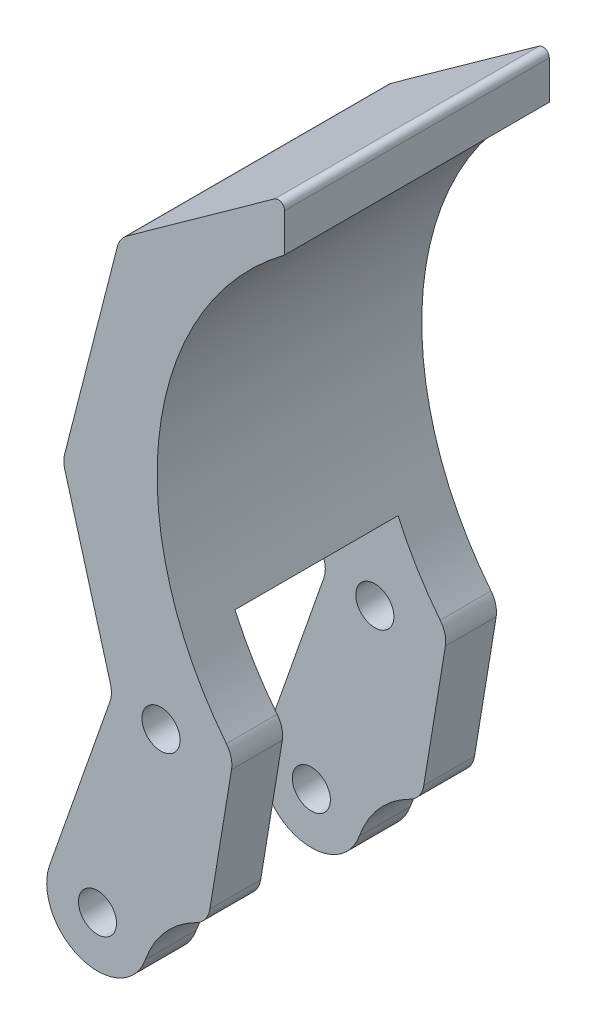
SolidWorks part; units mm, degrees
material "PMMA"
ref_plane "前视基准面" through (0, 0, 0) normal (0, 0, 1) x (1, 0, 0)
ref_plane "上视基准面" through (0, 0, 0) normal (0, 1, 0) x (1, 0, 0)
ref_plane "右视基准面" through (0, 0, 0) normal (1, 0, 0) x (0, 0, -1)
sketch "草图1" plane through (0, 0, 0) normal (0, 0, 1) x (1, 0, 0)
  line L1 (-44.759, 0) -> (37.6123, 0) construction
  line L2 (0, 0) -> (0, 68.6572) construction
  line L3 (23.6847, 21.3009) -> (7.0185, 2.6666) construction
  line L4 (29.6477, 15.9677) -> (12.9815, -2.6666) construction
  line L5 (30.4405, 19.9591) -> (22.8919, 17.3096) construction
  line L6 (16.1103, 33.6542) -> (17.8145, 23.2934) construction
  line L8 (30.4405, 19.9591) -> (25.6815, 33.5175) construction
  line L9 (25.6428, 34.7197) -> (29.2417, 47.5584) construction
  line L10 (29.2536, 48.5936) -> (25.1082, 64.8082) construction
  line L11 (19.8028, 35.3009) -> (3.1366, 16.6666) construction
  line L12 (23.5296, 31.9677) -> (6.8634, 13.3334) construction
  line L13 (24.3365, 65.9378) -> (12.7194, 74.273) construction
  line L14 (11.9279, 73.8667) -> (11.9279, 70.8409) construction
  line L15 (-23.6847, 21.3009) -> (-7.0185, 2.6666) construction
  line L16 (-29.6477, 15.9677) -> (-12.9815, -2.6666) construction
  line L17 (-23.5296, 31.9677) -> (-6.8634, 13.3334) construction
  line L18 (-19.8028, 35.3009) -> (-3.1366, 16.6666) construction
  line L19 (-16.1103, 33.6542) -> (-17.8145, 23.2934)
  line L20 (-30.4405, 19.9591) -> (-25.6815, 33.5175)
  line L25 (-25.6428, 34.7197) -> (-29.2417, 47.5584)
  line L26 (-5, 15) -> (-10, 0) construction
  line L27 (5, 15) -> (10, 0) construction
  line L28 (21.6662, 33.6343) -> (26.6662, 18.6343) construction
  line L29 (-29.2536, 48.5936) -> (-25.1082, 64.8082)
  line L30 (-24.3365, 65.9378) -> (-12.7194, 74.273)
  line L31 (-11.9279, 73.8667) -> (-11.9279, 70.8409)
  line L32 (-3.0291, 50.8087) -> (14.3488, 56.1034) construction
  circle A0 centre (-10, 0) radius 10 construction
  circle A4 centre (0, 51.7316) radius 15 construction
  circle A5 centre (10, 0) radius 4 construction
  circle A6 centre (10, 0) radius 10 construction
  arc A14 (22.8919, 17.3096) -> (17.993, 22.2086) centre (15.3434, 14.6601) ccw construction
  circle A16 centre (26.6662, 18.6343) radius 1.5 construction
  circle A17 centre (26.6662, 18.6343) radius 4 construction
  circle A18 centre (5, 15) radius 2.5 construction
  arc A19 (16.5198, 35.2255) -> (11.9279, 70.8409) centre (-3.0291, 50.8087) ccw construction
  circle A20 centre (21.6662, 33.6343) radius 2.5 construction
  circle A21 centre (-10, 0) radius 4 construction
  circle A22 centre (-26.6662, 18.6343) radius 1.5
  arc A23 (-30.4405, 19.9591) -> (-22.8919, 17.3096) centre (-26.6662, 18.6343) ccw
  arc A24 (-22.8919, 17.3096) -> (-18.8991, 21.8265) centre (-15.3434, 14.6601) cw
  circle A25 centre (-21.6662, 33.6343) radius 2.5 construction
  circle A26 centre (-5, 15) radius 2.5 construction
  circle A28 centre (-21.6662, 33.6343) radius 1.5
  circle A29 centre (-5, 15) radius 1.5 construction
  circle A30 centre (5, 15) radius 1.5 construction
  circle A31 centre (21.6662, 33.6343) radius 1.5 construction
  arc A33 (-18.8991, 21.8265) -> (-17.8145, 23.2934) centre (-19.788, 23.6181) ccw
  arc A40 (12.7194, 74.273) -> (11.9279, 73.8667) centre (12.4279, 73.8667) ccw construction
  arc A41 (18.8991, 21.8265) -> (17.8145, 23.2934) centre (19.788, 23.6181) cw construction
  arc A42 (16.1103, 33.6542) -> (16.5198, 35.2255) centre (18.0838, 33.9788) cw construction
  arc A43 (-16.5198, 35.2255) -> (-11.9279, 70.8409) centre (3.0291, 50.8087) cw
  arc A44 (25.6815, 33.5175) -> (25.6428, 34.7197) centre (27.5686, 34.1799) cw construction
  arc A45 (29.2417, 47.5584) -> (29.2536, 48.5936) centre (27.316, 48.0982) ccw construction
  arc A46 (25.1082, 64.8082) -> (24.3365, 65.9378) centre (23.1706, 64.3128) ccw construction
  arc A47 (-12.7194, 74.273) -> (-11.9279, 73.8667) centre (-12.4279, 73.8667) cw
  arc A48 (-16.1103, 33.6542) -> (-16.5198, 35.2255) centre (-18.0838, 33.9788) ccw
  arc A49 (-25.6815, 33.5175) -> (-25.6428, 34.7197) centre (-27.5686, 34.1799) ccw
  arc A50 (-29.2417, 47.5584) -> (-29.2536, 48.5936) centre (-27.316, 48.0982) cw
  arc A51 (-25.1082, 64.8082) -> (-24.3365, 65.9378) centre (-23.1706, 64.3128) cw
  point P93 (11.9279, 74.8409)
  point P96 (15.9627, 34.5512)
  point P99 (25.4726, 34.1125)
  point P102 (29.3864, 48.0744)
  point P105 (24.9279, 65.5135)
  point P109 (-11.9279, 74.8409)
  point P112 (-15.9627, 34.5512)
  point P115 (-25.4726, 34.1125)
  point P118 (-17.993, 22.2086)
  point P122 (-29.3864, 48.0744)
  point P125 (-24.9279, 65.5135)
  dimension "D1" = 30
  dimension "D3" = 20
  dimension "D4" = 25
  dimension "D5" = 8
  dimension "D6" = 3
  dimension "D7" = 2
  dimension "D8" = 8
  dimension "D13" = 25
  dimension "D20" = 140
  dimension "D21" = 5
  dimension "D27" = 3
  dimension "D29" = 0.5
  dimension "D28" = 16
  dimension "D30" = 2
  dimension "D14" = 4
  dimension "D12" = 10.5
  dimension "D18" = 150
  dimension "D10" = 0.5
  dimension "D26" = 2
  dimension "D9" = 11
  dimension "D11" = 15
  dimension "D15" = 10
  dimension "D16" = 145
  dimension "D17" = 14.5
  dimension "D19" = 18
  dimension "D22" = 5
  dimension "D23" = 15
  dimension "D24" = 25
  dimension "D25" = 3.75
extrude "凸台-拉伸1" add sketch "草图1" along normal blind 4
sketch "草图2" plane through (0, 0, 0) normal (0, 0, 1) x (1, 0, 0)
  line L0 (-26.7731, 38.7518) -> (-19.8346, 40.6968)
  line L1 (-29.2417, 47.5584) -> (-26.7731, 38.7518)
  line L6 (-11.9279, 70.8409) -> (-11.9279, 73.8667)
  line L7 (-12.7194, 74.273) -> (-24.3365, 65.9378)
  line L8 (-25.1082, 64.8082) -> (-29.2536, 48.5936)
  line L9 (-29.2417, 47.5584) -> (-25.6428, 34.7197)
  line L10 (-25.6815, 33.5175) -> (-30.4405, 19.9591)
  line L11 (-17.8145, 23.2934) -> (-16.1103, 33.6542)
  line L12 (-11.9279, 70.8409) -> (-11.9279, 73.8667)
  line L13 (-12.7194, 74.273) -> (-24.3365, 65.9378)
  line L14 (-25.1082, 64.8082) -> (-29.2536, 48.5936)
  arc A9 (-11.9279, 70.8409) -> (-16.5198, 35.2255) centre (3.0291, 50.8087) ccw
  arc A10 (-11.9279, 73.8667) -> (-12.7194, 74.273) centre (-12.4279, 73.8667) ccw
  arc A11 (-24.3365, 65.9378) -> (-25.1082, 64.8082) centre (-23.1706, 64.3128) ccw
  arc A12 (-29.2536, 48.5936) -> (-29.2417, 47.5584) centre (-27.316, 48.0982) ccw
  arc A13 (-25.6815, 33.5175) -> (-25.6428, 34.7197) centre (-27.5686, 34.1799) ccw
  arc A14 (-30.4405, 19.9591) -> (-22.8919, 17.3096) centre (-26.6662, 18.6343) ccw
  arc A15 (-18.8991, 21.8265) -> (-22.8919, 17.3096) centre (-15.3434, 14.6601) ccw
  arc A16 (-18.8991, 21.8265) -> (-17.8145, 23.2934) centre (-19.788, 23.6181) ccw
  arc A17 (-16.1103, 33.6542) -> (-16.5198, 35.2255) centre (-18.0838, 33.9788) ccw
  arc A18 (-11.9279, 70.8409) -> (-19.8346, 40.6968) centre (3.0291, 50.8087) ccw
  arc A19 (-11.9279, 73.8667) -> (-12.7194, 74.273) centre (-12.4279, 73.8667) ccw
  arc A20 (-24.3365, 65.9378) -> (-25.1082, 64.8082) centre (-23.1706, 64.3128) ccw
  arc A21 (-29.2536, 48.5936) -> (-29.2417, 47.5584) centre (-27.316, 48.0982) ccw
  dimension "D1" = 0
extrude "凸台-拉伸2" add sketch "草图2" along normal blind 20.84
ref_plane "基准面1" through (0, 0, 20.84) normal (0, 0, 1) x (1, 0, 0)
sketch "草图5" plane through (0, 0, 20.84) normal (0, 0, 1) x (1, 0, 0)
  line L4 (-19.8346, 40.6968) -> (-26.7731, 38.7518)
  line L5 (-26.7731, 38.7518) -> (-25.6428, 34.7197)
  line L6 (-25.6815, 33.5175) -> (-30.4405, 19.9591)
  line L7 (-17.8145, 23.2934) -> (-16.1103, 33.6542)
  line L8 (-19.8346, 40.6968) -> (-26.7731, 38.7518)
  line L9 (-26.7731, 38.7518) -> (-25.6428, 34.7197)
  line L10 (-25.6815, 33.5175) -> (-30.4405, 19.9591)
  line L11 (-17.8145, 23.2934) -> (-16.1103, 33.6542)
  arc A6 (-25.6815, 33.5175) -> (-25.6428, 34.7197) centre (-27.5686, 34.1799) ccw
  arc A7 (-30.4405, 19.9591) -> (-22.8919, 17.3096) centre (-26.6662, 18.6343) ccw
  arc A8 (-18.8991, 21.8265) -> (-22.8919, 17.3096) centre (-15.3434, 14.6601) ccw
  arc A9 (-18.8991, 21.8265) -> (-17.8145, 23.2934) centre (-19.788, 23.6181) ccw
  arc A10 (-16.1103, 33.6542) -> (-16.5198, 35.2255) centre (-18.0838, 33.9788) ccw
  arc A11 (-19.8346, 40.6968) -> (-16.5198, 35.2255) centre (3.0291, 50.8087) ccw
  arc A12 (-25.6815, 33.5175) -> (-25.6428, 34.7197) centre (-27.5686, 34.1799) ccw
  arc A13 (-30.4405, 19.9591) -> (-22.8919, 17.3096) centre (-26.6662, 18.6343) ccw
  arc A14 (-18.8991, 21.8265) -> (-22.8919, 17.3096) centre (-15.3434, 14.6601) ccw
  arc A15 (-18.8991, 21.8265) -> (-17.8145, 23.2934) centre (-19.788, 23.6181) ccw
  arc A16 (-16.1103, 33.6542) -> (-16.5198, 35.2255) centre (-18.0838, 33.9788) ccw
  arc A17 (-19.8346, 40.6968) -> (-16.5198, 35.2255) centre (3.0291, 50.8087) ccw
  dimension "D1" = 0
extrude "凸台-拉伸3" add sketch "草图5" against normal blind 4
ref_plane "基准面2" through (0, 0, 0) normal (0, 0, -1) x (-1, 0, 0)
sketch "草图8" plane through (0, 0, 0) normal (0, 0, -1) x (-1, 0, 0)
  circle A0 centre (21.6662, 33.6343) radius 1.5
  circle A1 centre (26.6662, 18.6343) radius 1.5
extrude "切除-拉伸1" cut sketch "草图8" against normal through all
